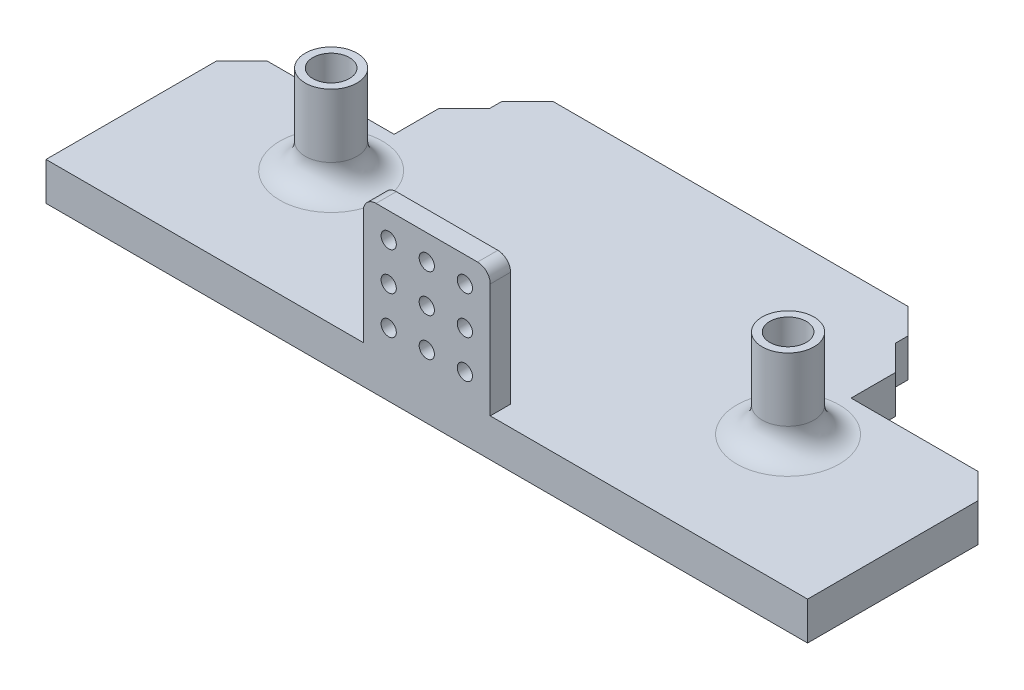
SolidWorks part; units mm, degrees
ref_plane "Front Plane" through (0, 0, 0) normal (0, 0, 1) x (1, 0, 0)
ref_plane "Top Plane" through (0, 0, 0) normal (0, 1, 0) x (1, 0, 0)
ref_plane "Right Plane" through (0, 0, 0) normal (1, 0, 0) x (0, 0, -1)
sketch "Sketch1" plane through (0, 0, 0) normal (0, 1, 0) x (1, 0, 0)
  line L1 (-75, 26.16) -> (75, 26.16)
  line L2 (-75, 26.16) -> (-75, -26.16)
  line L3 (-75, -26.16) -> (75, -26.16)
  line L4 (75, 26.16) -> (75, -26.16)
  line L5 (-75, 26.16) -> (75, -26.16) construction
  line L6 (-75, -26.16) -> (75, 26.16) construction
  point P0 (0, 0)
  dimension "D1" = 52.32
  dimension "D2" = 150
extrude "Boss-Extrude1" add sketch "Sketch1" along normal blind 7.5
sketch "Sketch2" plane through (0, 7.5, 0) normal (0, 1, 0) x (1, 0, 0)
  line L0 (-75, 0) -> (75, 0) construction
  line L1 (-75, 26.16) -> (-75, -26.16) construction
  line L2 (75, -26.16) -> (75, 26.16) construction
  circle A0 centre (-45, 0) radius 5.1
  circle A1 centre (45, 0) radius 5.1
  dimension "D1" = 30
  dimension "D2" = 30
extrude "Boss-Extrude2" add sketch "Sketch2" along normal blind 17.5
fillet "Fillet1" radius 5 2 edges at (45, 7.5, 5.1) (-45, 7.5, 5.1)
sketch "Sketch3" plane through (0, 25, 0) normal (0, 1, 0) x (1, 0, 0)
  circle A0 centre (-45, 0) radius 3.6
  circle A1 centre (45, 0) radius 3.6
extrude "Cut-Extrude1" cut sketch "Sketch3" against normal blind 25
sketch "Sketch4" plane through (0, 0, -26.16) normal (0, 0, -1) x (-1, 0, 0)
  line L0 (-75, 0) -> (75, 0) construction
  line L1 (-75, 7.5) -> (-45, 7.5)
  line L2 (-75, 7.5) -> (-75, 0)
  line L3 (-75, 0) -> (-45, 0)
  line L4 (-45, 7.5) -> (-45, 0)
  line L6 (75, 7.5) -> (45, 7.5)
  line L7 (75, 7.5) -> (75, 0)
  line L8 (75, 0) -> (45, 0)
  line L9 (45, 7.5) -> (45, 0)
  dimension "D1" = 30
  dimension "D2" = 30
extrude "Cut-Extrude2" cut sketch "Sketch4" against normal blind 13.75
chamfer "Chamfer1" distance 5 angle 45 4 edges at (75, 3.75, -12.41) (45, 3.75, -26.16) (-45, 3.75, -26.16) (-75, 3.75, -12.41)
sketch "Sketch5" plane through (0, 0, -26.16) normal (0, 0, -1) x (-1, 0, 0)
  line L1 (-40, 7.5) -> (40, 7.5)
  line L2 (-40, 7.5) -> (-40, 0)
  line L3 (-40, 0) -> (40, 0)
  line L4 (40, 7.5) -> (40, 0)
extrude "Boss-Extrude3" add sketch "Sketch5" along normal blind 7.5
chamfer "Chamfer2" distance 5 angle 45 2 edges at (40, 3.75, -33.66) (-40, 3.75, -33.66)
sketch "Sketch6" plane through (0, 0, -33.66) normal (0, 0, -1) x (-1, 0, 0)
  line L0 (-35, 3.75) -> (35, 3.75) construction
  line L1 (-35, 7.5) -> (-35, 0) construction
  line L2 (35, 0) -> (35, 7.5) construction
  circle A0 centre (-15, 3.75) radius 1.5
  circle A1 centre (15, 3.75) radius 1.5
  point P10 (0, 3.75)
  dimension "D1" = 15
  dimension "D2" = 15
extrude "Cut-Extrude3" cut sketch "Sketch6" against normal blind 7.5
sketch "Sketch7" plane through (0, 7.5, 0) normal (0, 1, 0) x (1, 0, 0)
  line L0 (0, -26.16) -> (0, 33.66) construction
  line L1 (-75, -26.16) -> (75, -26.16) construction
  line L2 (-35, 33.66) -> (35, 33.66) construction
  line L3 (-43.2004, -21.16) -> (-25.6652, -21.16) construction
  line L4 (-12.5, -22.16) -> (-12.5, -26.16) construction
  line L5 (12.5, -22.16) -> (12.5, -26.16) construction
  line L7 (-12.5, -22.16) -> (12.5, -22.16)
  line L8 (-12.5, -22.16) -> (-12.5, -26.16)
  line L9 (-12.5, -26.16) -> (12.5, -26.16)
  line L10 (12.5, -22.16) -> (12.5, -26.16)
  dimension "D1" = 5
  dimension "D2" = 12.5
  dimension "D3" = 12.5
  dimension "D4" = 4
extrude "Boss-Extrude4" add sketch "Sketch7" along normal blind 25
sketch "Sketch8" plane through (0, 0, 22.16) normal (0, 0, -1) x (-1, 0, 0)
  line L0 (-12.5, 31.25) -> (12.5, 31.25) construction
  line L1 (-12.5, 32.5) -> (-12.5, 7.5) construction
  line L2 (12.5, 32.5) -> (12.5, 7.5) construction
  line L3 (-12.5, 32.5) -> (12.5, 32.5) construction
  line L4 (-12.5, 8.75) -> (12.5, 8.75) construction
  line L5 (-11.25, 32.5) -> (-11.25, 8.75) construction
  line L6 (11.25, 32.5) -> (11.25, 8.75) construction
  line L7 (0, 31.25) -> (0, 8.75) construction
  line L8 (-3.75, 31.25) -> (-3.75, 8.75) construction
  line L9 (3.75, 31.25) -> (3.75, 8.75) construction
  line L10 (-11.25, 23.75) -> (11.25, 23.75) construction
  line L11 (-11.25, 16.25) -> (11.25, 16.25) construction
  line L12 (-7.5, 31.25) -> (-7.5, 8.75) construction
  line L13 (7.5, 31.25) -> (7.5, 8.75) construction
  line L14 (-11.25, 27.5) -> (11.25, 27.5) construction
  line L15 (-11.25, 12.5) -> (11.25, 12.5) construction
  circle A0 centre (-7.5, 20) radius 1.5
  circle A1 centre (0, 20) radius 1.5
  circle A2 centre (-7.5, 27.5) radius 1.5
  circle A3 centre (0, 27.5) radius 1.5
  circle A4 centre (7.5, 27.5) radius 1.5
  circle A5 centre (7.5, 20) radius 1.5
  circle A6 centre (-7.5, 12.5) radius 1.5
  circle A7 centre (0, 12.5) radius 1.5
  circle A8 centre (7.5, 12.5) radius 1.5
  dimension "D10" = 3.75
  dimension "D12" = 3.75
  dimension "D1" = 1.25
  dimension "D2" = 1.25
  dimension "D3" = 1.25
  dimension "D4" = 1.25
  dimension "D5" = 3.75
  dimension "D6" = 3.75
  dimension "D7" = 7.5
  dimension "D8" = 7.5
  dimension "D9" = 3.75
  dimension "D11" = 3.75
extrude "Cut-Extrude4" cut sketch "Sketch8" against normal blind 5
fillet "Fillet2" radius 2.5 2 edges at (12.5, 32.5, 24.16) (-12.5, 32.5, 24.16)
